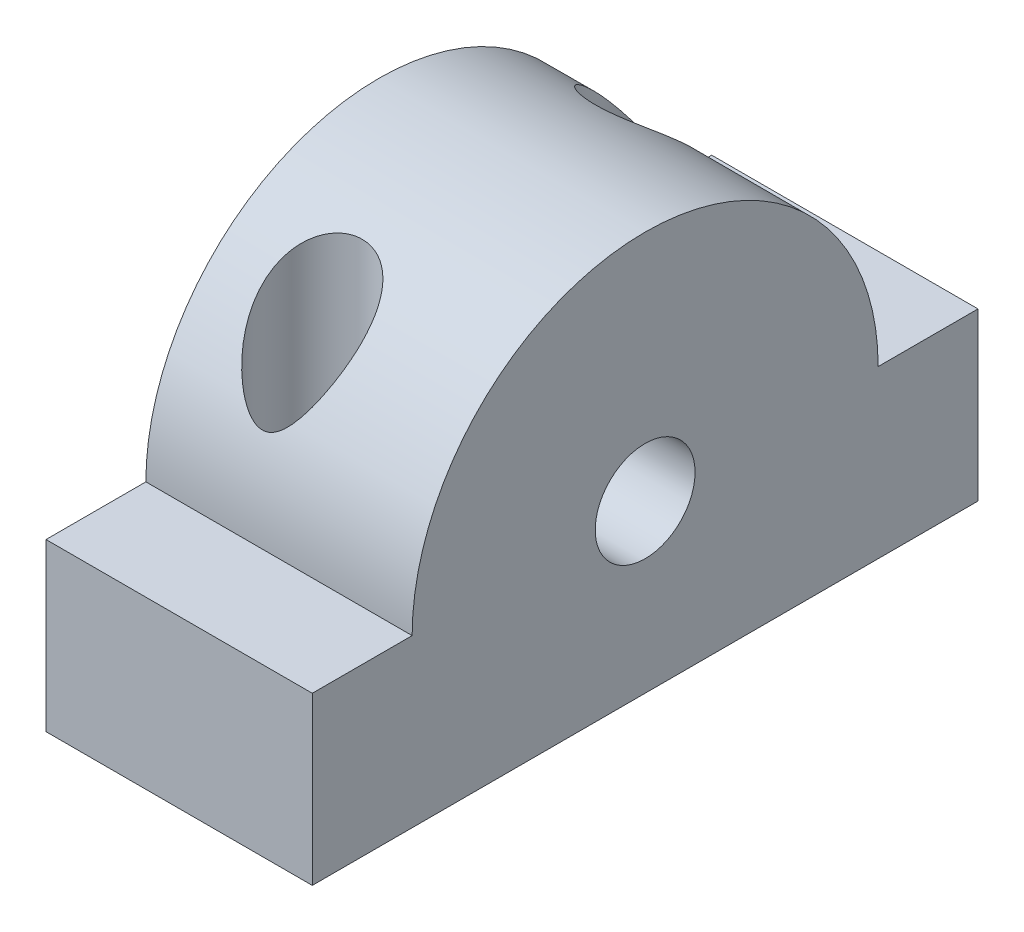
SolidWorks part; units mm, degrees
ref_plane "Front Plane" through (0, 0, 0) normal (0, 0, 1) x (1, 0, 0)
ref_plane "Top Plane" through (0, 0, 0) normal (0, 1, 0) x (1, 0, 0)
ref_plane "Right Plane" through (0, 0, 0) normal (1, 0, 0) x (0, 0, -1)
sketch "Sketch1" plane through (0, 0, 0) normal (1, 0, 0) x (0, 0, -1)
  line L0 (17, 0) -> (20, 0)
  line L1 (0, 0) -> (3, 0)
  line L2 (0, 0) -> (0, -5)
  line L3 (0, -5) -> (20, -5)
  line L4 (20, 0) -> (20, -5)
  arc A1 (17, 0) -> (3, 0) centre (10, 0) ccw
  dimension "D1" = 5
  dimension "D4" = 7
  dimension "D2" = 20
  dimension "D3" = 10
extrude "Boss-Extrude1" add sketch "Sketch1" along normal blind 8
sketch "Sketch2" plane through (8, 0, 0) normal (1, 0, 0) x (0, 0, -1)
  circle A0 centre (10, 0) radius 2
  dimension "D1" = 4
extrude "Boss-Extrude2" [suppressed] add sketch "Sketch2" against normal blind 8
sketch "Sketch3" plane through (0, -5, 0) normal (0, -1, 0) x (1, 0, 0)
  line L0 (0, -10) -> (8, -10) construction
  line L1 (0, 0) -> (0, -20) construction
  line L2 (8, 0) -> (8, -20) construction
  circle A0 centre (3, -5) radius 1.5
  circle A1 centre (3, -15) radius 1.5
  dimension "D1" = 3
  dimension "D2" = 3
  dimension "D3" = 5
extrude "Cut-Extrude1" cut sketch "Sketch3" against normal blind 15
sketch "Sketch4" plane through (8, 0, 0) normal (1, 0, 0) x (0, 0, -1)
  circle A1 centre (10, 0) radius 1.5
  dimension "D1" = 3
extrude "Cut-Extrude2" cut sketch "Sketch4" against normal blind 10
